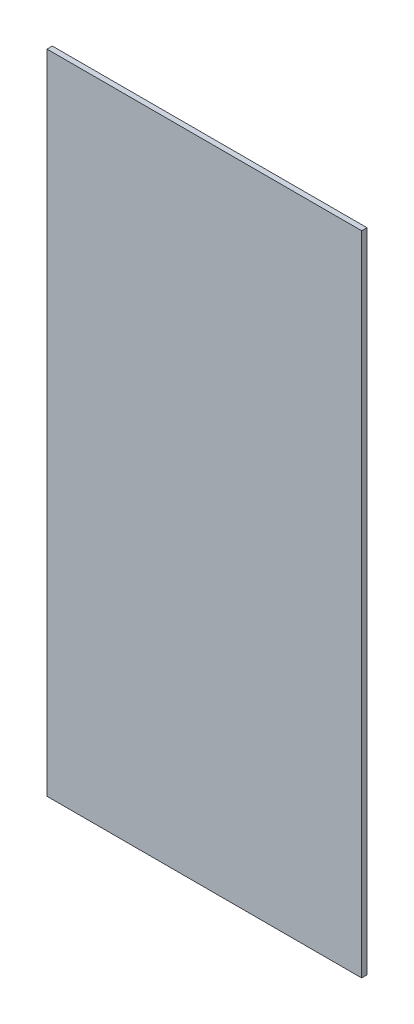
SolidWorks part; units mm, degrees
ref_plane "Front Plane" through (0, 0, 0) normal (0, 0, 1) x (1, 0, 0)
ref_plane "Top Plane" through (0, 0, 0) normal (0, 1, 0) x (1, 0, 0)
ref_plane "Right Plane" through (0, 0, 0) normal (1, 0, 0) x (0, 0, -1)
sketch "Sketch1" plane through (0, 0, 0) normal (0, 0, 1) x (1, 0, 0)
  line L1 (0, 0) -> (890, 0)
  line L2 (0, 0) -> (0, 1830)
  line L3 (0, 1830) -> (890, 1830)
  line L4 (890, 0) -> (890, 1830)
  dimension "D1" = 1830
  dimension "D2" = 890
extrude "Boss-Extrude1" add sketch "Sketch1" along normal blind 15
